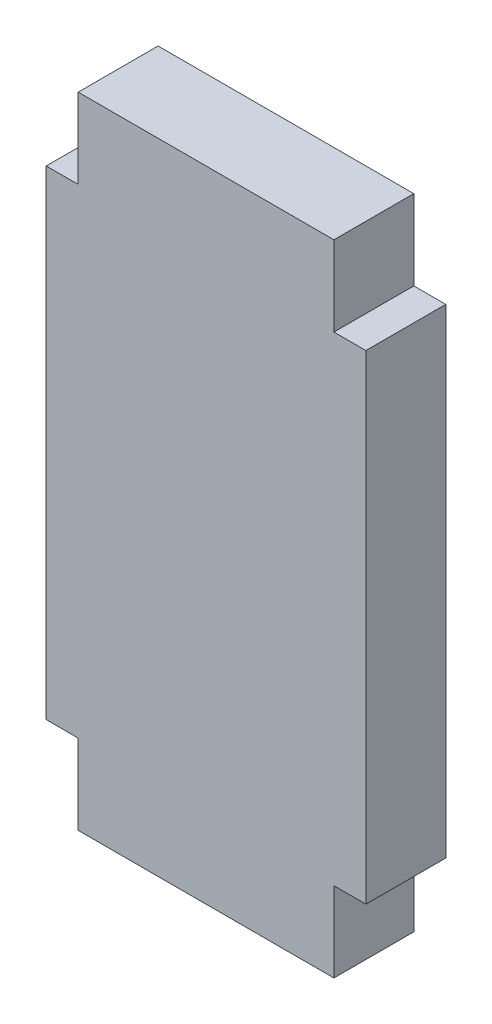
SolidWorks part; units mm, degrees
ref_plane "Front Plane" through (0, 0, 0) normal (0, 0, 1) x (1, 0, 0)
ref_plane "Top Plane" through (0, 0, 0) normal (0, 1, 0) x (1, 0, 0)
ref_plane "Right Plane" through (0, 0, 0) normal (1, 0, 0) x (0, 0, -1)
sketch "Sketch1" plane through (0, 0, 0) normal (0, 0, 1) x (1, 0, 0)
  line L0 (-8, -15) -> (-10, -15)
  line L1 (8, 20) -> (-8, 20)
  line L2 (8, 20) -> (8, 15)
  line L3 (8, -20) -> (-8, -20)
  line L4 (-8, 20) -> (-8, 15)
  line L5 (8, 20) -> (-8, -20) construction
  line L6 (8, -20) -> (-8, 20) construction
  line L7 (10, 15) -> (8, 15)
  line L8 (10, 15) -> (10, -15)
  line L9 (10, -15) -> (8, -15)
  line L10 (-10, 15) -> (-10, -15)
  line L11 (10, 15) -> (-10, -15) construction
  line L12 (10, -15) -> (-10, 15) construction
  line L13 (8, -15) -> (8, -20)
  line L14 (-8, -15) -> (-8, -20)
  line L15 (-8, 15) -> (-10, 15)
  point P0 (0, 0)
  point P6 (0, 0)
  dimension "D1" = 40
  dimension "D2" = 16
  dimension "D3" = 20
  dimension "D4" = 30
extrude "Boss-Extrude1" add sketch "Sketch1" along normal blind 5
